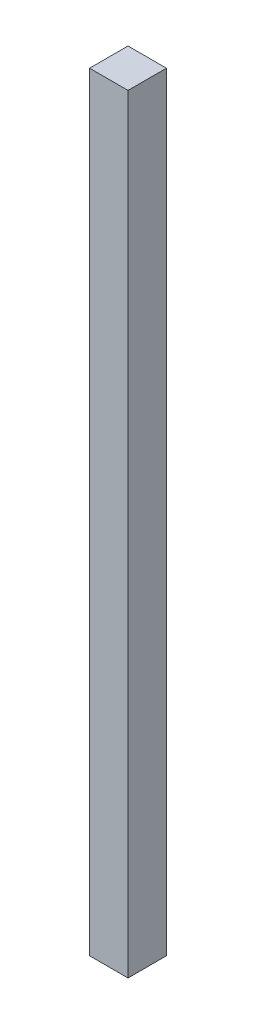
SolidWorks part; units mm, degrees
ref_plane "Front Plane" through (0, 0, 0) normal (0, 0, 1) x (1, 0, 0)
ref_plane "Top Plane" through (0, 0, 0) normal (0, 1, 0) x (1, 0, 0)
ref_plane "Right Plane" through (0, 0, 0) normal (1, 0, 0) x (0, 0, -1)
sketch "Sketch1" plane through (0, 0, 0) normal (0, 1, 0) x (1, 0, 0)
  line L1 (0, 0) -> (5, 0)
  line L2 (0, 0) -> (0, 5)
  line L3 (0, 5) -> (5, 5)
  line L4 (5, 0) -> (5, 5)
  dimension "D1" = 5
extrude "Boss-Extrude1" add sketch "Sketch1" along normal blind 100
